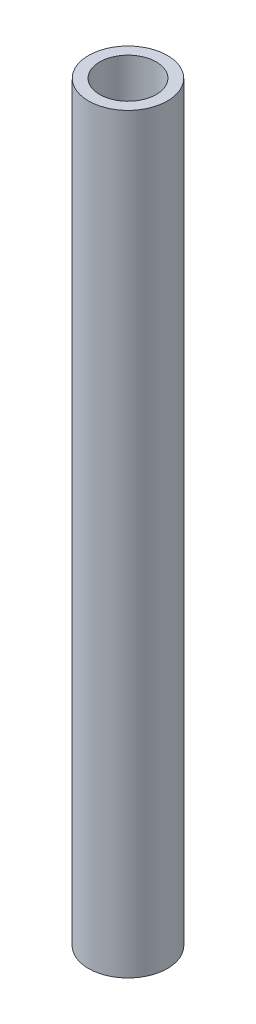
SolidWorks part; units mm, degrees
ref_plane "Front Plane" through (0, 0, 0) normal (0, 0, 1) x (1, 0, 0)
ref_plane "Top Plane" through (0, 0, 0) normal (0, 1, 0) x (1, 0, 0)
ref_plane "Right Plane" through (0, 0, 0) normal (1, 0, 0) x (0, 0, -1)
sketch "Sketch1" plane through (0, 0, 0) normal (0, 1, 0) x (1, 0, 0)
  circle A0 centre (0, 0) radius 7.6454
  circle A1 centre (0, 0) radius 10.668
  dimension "D1" = 21.336
  dimension "D2" = 15.2908
extrude "Boss-Extrude1" add sketch "Sketch1" along normal blind 203.2
